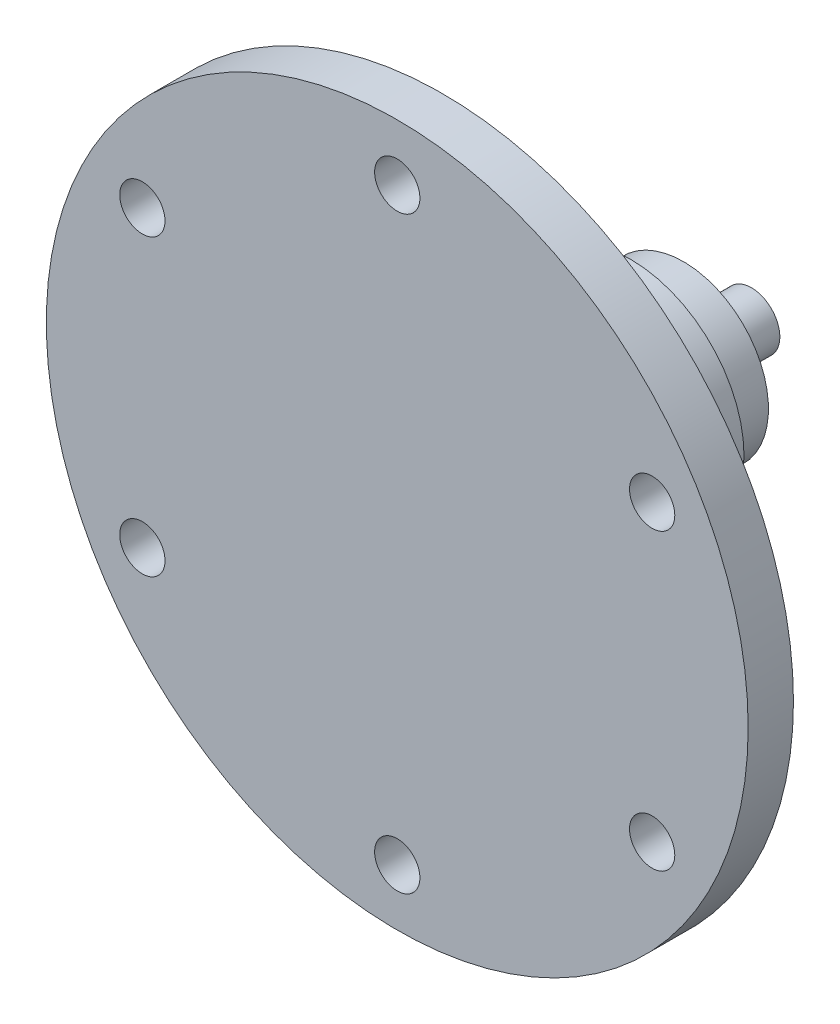
SolidWorks part; units mm, degrees
ref_plane "Front Plane" through (0, 0, 0) normal (0, 0, 1) x (1, 0, 0)
ref_plane "Top Plane" through (0, 0, 0) normal (0, 1, 0) x (1, 0, 0)
ref_plane "Right Plane" through (0, 0, 0) normal (1, 0, 0) x (0, 0, -1)
sketch "Sketch1" plane through (0, 0, 0) normal (0, 0, 1) x (1, 0, 0)
  line L0 (0, 21) -> (0, 26) construction
  circle A0 centre (0, 0) radius 31
  circle A2 centre (0, 26) radius 2
  circle A3 centre (22.5167, 13) radius 2
  circle A4 centre (22.5167, -13) radius 2
  circle A5 centre (0, -26) radius 2
  circle A6 centre (-22.5167, -13) radius 2
  circle A7 centre (-22.5167, 13) radius 2
  point P19 (0, 0)
  dimension "D1" = 62
  dimension "D3" = 5
  dimension "D4" = 4
  dimension "D5" = 6
extrude "Boss-Extrude1" add sketch "Sketch1" along normal blind 4
sketch "Sketch2" plane through (0, 0, 0) normal (0, 0, -1) x (-1, 0, 0)
  circle A0 centre (0, 0) radius 22.5
  dimension "D1" = 45
extrude "Boss-Extrude2" add sketch "Sketch2" along normal blind 4.63
sketch "Sketch3" plane through (0, 0, -4.63) normal (0, 0, -1) x (-1, 0, 0)
  circle A0 centre (0, 0) radius 10
  dimension "D1" = 20
extrude "Boss-Extrude3" add sketch "Sketch3" along normal blind 12
sketch "Sketch4" plane through (0, 0, -16.63) normal (0, 0, -1) x (-1, 0, 0)
  circle A0 centre (0, 0) radius 7.5
  dimension "D1" = 15
extrude "Boss-Extrude4" add sketch "Sketch4" along normal blind 4.66
sketch "Sketch7" plane through (0, 0, -21.29) normal (0, 0, -1) x (-1, 0, 0)
  circle A0 centre (0, 0) radius 2.505
  dimension "D1" = 5.01
extrude "Boss-Extrude5" add sketch "Sketch7" along normal blind 6
